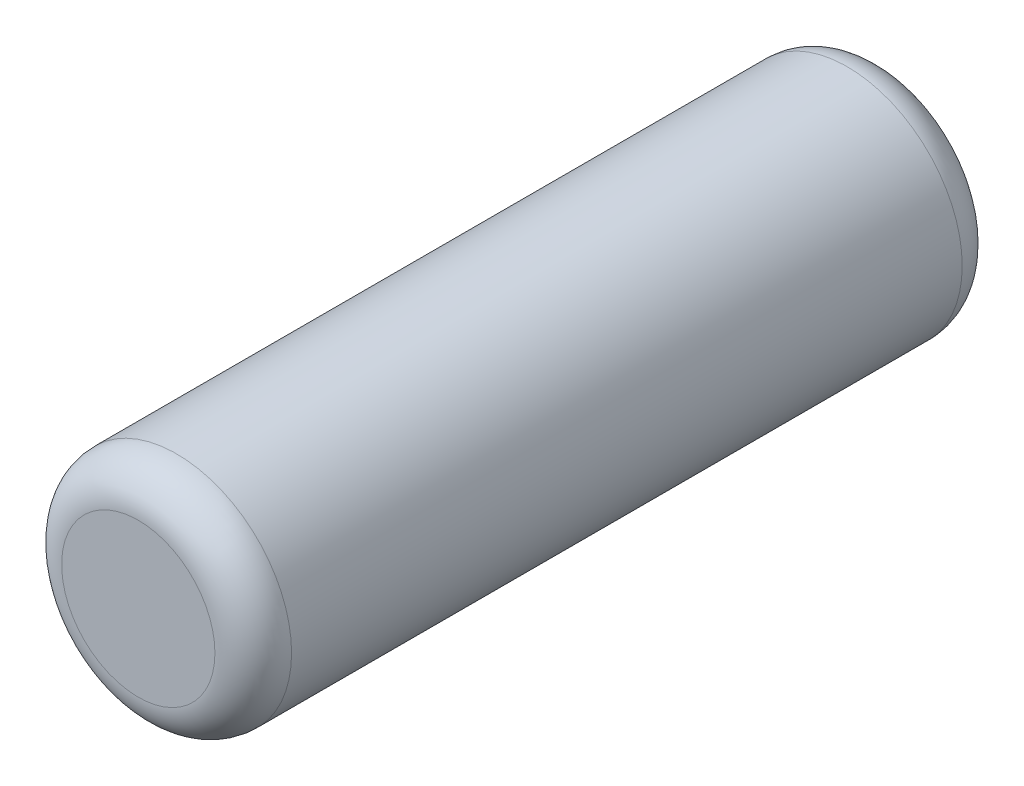
SolidWorks part; units mm, degrees
material "ABS"
ref_plane "正面" through (0, 0, 0) normal (0, 0, 1) x (1, 0, 0)
ref_plane "平面" through (0, 0, 0) normal (0, 1, 0) x (1, 0, 0)
ref_plane "右側面" through (0, 0, 0) normal (1, 0, 0) x (0, 0, -1)
sketch "ｽｹｯﾁ1" plane through (0, 0, 0) normal (0, 0, 1) x (1, 0, 0)
  circle A0 centre (0, 0) radius 3
  dimension "6" = 6
extrude "ﾎﾞｽ - 押し出し1" add sketch "ｽｹｯﾁ1" along normal blind 19.5
fillet "ﾌｨﾚｯﾄ1" radius 1 2 edges at (3, 0, 0) (3, 0, 19.5)
